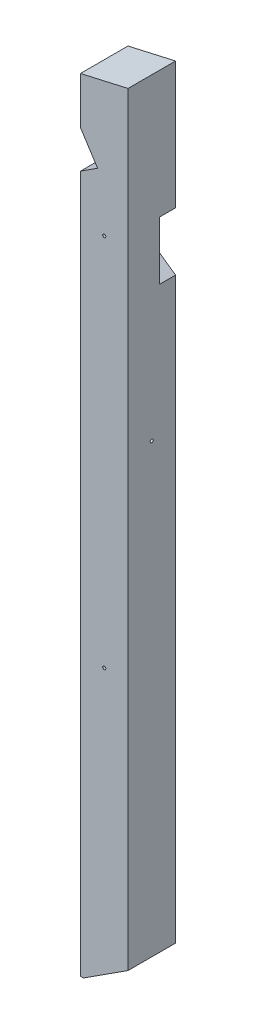
SolidWorks part; units mm, degrees
material "Pine"
ref_plane "Front Plane" through (0, 0, 0) normal (0, 0, 1) x (1, 0, 0)
ref_plane "Top Plane" through (0, 0, 0) normal (0, 1, 0) x (1, 0, 0)
ref_plane "Right Plane" through (0, 0, 0) normal (1, 0, 0) x (0, 0, -1)
sketch "Sketch1" plane through (0, 0, 0) normal (0, 1, 0) x (1, 0, 0)
  line L1 (-75, 75) -> (75, 75)
  line L2 (-75, 75) -> (-75, -75)
  line L3 (-75, -75) -> (75, -75)
  line L4 (75, 75) -> (75, -75)
  line L5 (-75, 75) -> (75, -75) construction
  line L6 (-75, -75) -> (75, 75) construction
  point P0 (0, 0)
  dimension "D1" = 150
  dimension "D2" = 150
extrude "Boss-Extrude1" add sketch "Sketch1" along normal mid plane 2500
sketch "Sketch2" plane through (0, 0, 75) normal (0, 0, 1) x (1, 0, 0)
  circle A0 centre (0, 810) radius 5
  circle A1 centre (0, -370) radius 5
  dimension "D1" = 10
  dimension "D2" = 810
  dimension "D3" = 370
extrude "Bolts" cut sketch "Sketch2" against normal through all
sketch "Sketch3" plane through (0, 0, 75) normal (0, 0, 1) x (1, 0, 0)
  line L0 (-75, 1068.1592) -> (-20.8483, 984.0902)
  line L1 (-75, 1250) -> (-75, -1250) construction
  line L2 (-20.8483, 984.0902) -> (-75, 1068.1592) construction
  line L3 (-20.8483, 984.0902) -> (-75, 949.2092)
  line L4 (-104.9172, 929.9385) -> (-20.8483, 984.0902) construction
  line L5 (-75, 949.2092) -> (-75, 1068.1592)
extrude "TopCut" cut sketch "Sketch3" against normal through all
sketch "Sketch4" plane through (0, 0, 75) normal (0, 0, 1) x (1, 0, 0)
  line L0 (75, 1250) -> (-75, 1215.9567)
  line L1 (-75, 1250) -> (-75, 1068.1592) construction
  line L2 (-1060.1484, 992.3717) -> (402.6511, 1324.3622) construction
  line L3 (-75, 1215.9567) -> (-75, 1250)
  line L4 (-75, 1250) -> (75, 1250)
extrude "RoofCut" cut sketch "Sketch4" against normal through all
sketch "Sketch5" plane through (0, 0, 75) normal (0, 0, 1) x (1, 0, 0)
  line L0 (75, -1159.4702) -> (-65.5448, -1250)
  line L1 (75, 1250) -> (75, -1250) construction
  line L2 (-185.8401, -1327.4864) -> (1915.8839, 26.3068) construction
  line L3 (-75, -1250) -> (75, -1250) construction
  line L4 (-65.5448, -1250) -> (75, -1250)
  line L5 (75, -1250) -> (75, -1159.4702)
extrude "Cut-Extrude4" cut sketch "Sketch5" against normal through all
sketch "Sketch6" plane through (-75, 0, 0) normal (-1, 0, 0) x (0, 0, 1)
  circle A0 centre (0, 250) radius 5
  dimension "D1" = 10
  dimension "D2" = 250
extrude "Cut-Extrude5" cut sketch "Sketch6" against normal through all
sketch "Sketch7" plane through (0, 0, -75) normal (0, 0, -1) x (-1, 0, 0)
  line L0 (-75, 665.3023) -> (75.5005, 771.4789)
  line L1 (-75, 1250) -> (-75, -1159.4702) construction
  line L2 (552.0582, 1107.6856) -> (-762.2409, 180.4607) construction
  line L3 (75.5005, 771.4789) -> (75, 954.6977)
  line L4 (75, 104.3414) -> (75, 1067.9986) construction
  line L5 (-569.3567, 500.1105) -> (124.6885, 989.7524) construction
  line L6 (75, 954.6977) -> (-75, 848.8742)
  line L7 (-75, 848.8742) -> (-75, 665.3023)
extrude "Cut-Extrude6" cut sketch "Sketch7" against normal blind 50
